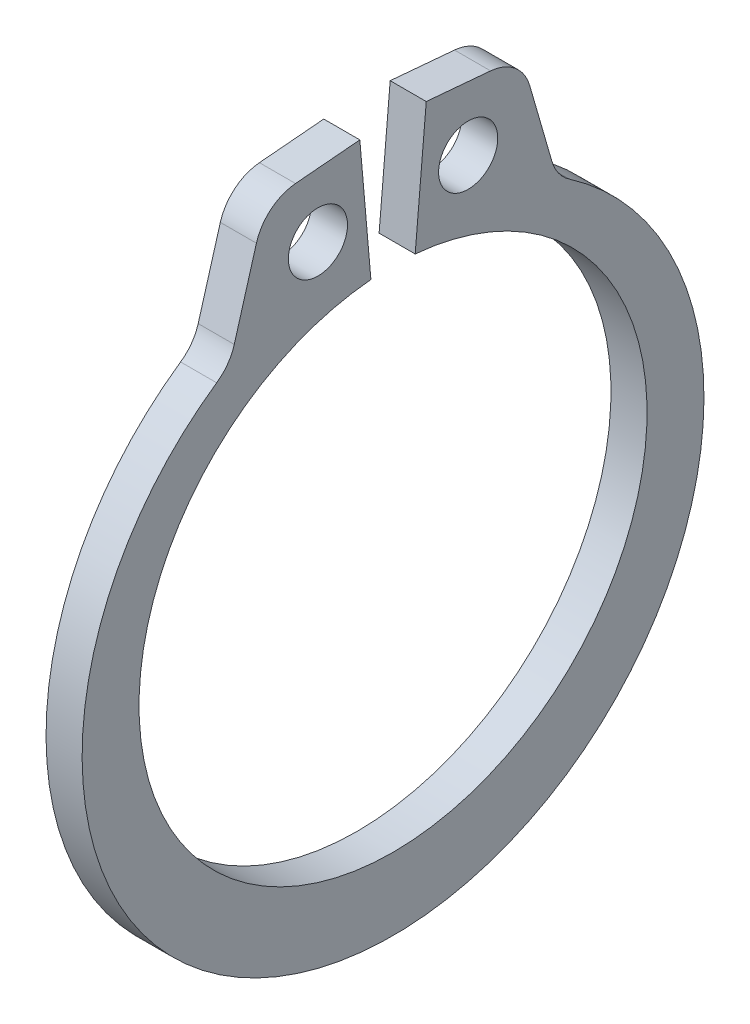
SolidWorks part; units mm, degrees
material "Cast Carbon Steel"
ref_plane "Front" through (0, 0, 0) normal (0, 0, 1) x (1, 0, 0)
ref_plane "Top" through (0, 0, 0) normal (0, 1, 0) x (1, 0, 0)
ref_plane "Right" through (0, 0, 0) normal (1, 0, 0) x (0, 0, -1)
sketch "Sketch1" plane through (0, 0, 0) normal (1, 0, 0) x (0, 0, -1)
  line L0 (0, 0) -> (0, 4.4704) construction
  line L1 (-0.3896, 4.4534) -> (-0.5844, 6.6801)
  line L2 (0.5844, 6.6801) -> (2.2545, 6.534)
  line L3 (2.2545, 6.534) -> (2.8753, 4.3867)
  line L4 (0.3896, 4.4534) -> (0.5844, 6.6801)
  line L5 (-0.5844, 6.6801) -> (-2.2545, 6.534)
  line L6 (-2.2545, 6.534) -> (-2.8753, 4.3867)
  line L7 (-2.8753, 4.3867) -> (-2.4507, 3.7388) construction
  line L8 (2.8753, 4.3867) -> (2.4507, 3.7388) construction
  line L9 (0, -4.4704) -> (0, -5.7404) construction
  line L10 (-2.2545, 6.534) -> (-0.3896, 4.4534) construction
  line L11 (0, 4.4704) -> (0, 6.7056) construction
  line L12 (-4.4704, 0) -> (4.4704, 0) construction
  circle A0 centre (0, 0) radius 4.4704 construction
  arc A1 (-0.3896, 4.4534) -> (0.3896, 4.4534) centre (0, 0) ccw
  circle A3 centre (0, 0) radius 7.493 construction
  circle A4 centre (-1.322, 5.4937) radius 0.5207
  circle A5 centre (1.322, 5.4937) radius 0.5207
  arc A6 (-2.8753, 4.3867) -> (2.8753, 4.3867) centre (0, -0.2686) ccw
  point P0 (0, -5.7404)
  dimension "A" = 8.9408
  dimension "Hole" = 1.0414
  dimension "Smin" = 0.7747
  dimension "H" = 2.2352
  dimension "D2" = 1.6764
  dimension "Angle" = 5
extrude "Extrude1" add sketch "Sketch1" along normal mid plane 0.635
fillet "Fillet1" radius 0.7874 4 edges at (0, 4.3867, 2.8753) (0, 4.3867, -2.8753) (0, 6.534, 2.2545) (0, 6.534, -2.2545)
sketch "Sketch2" plane through (0, 0, 0) normal (0, 0, 1) x (1, 0, 0)
  line L0 (-3.5433, 0) -> (9.1567, 0)
  line L1 (9.1567, 0) -> (9.1567, -4.7625)
  line L2 (-0.3683, -4.7625) -> (-3.2512, -4.7625)
  line L3 (9.1567, -4.7625) -> (0.3683, -4.7625)
  line L4 (0.3683, -4.7625) -> (0.3683, -4.4704)
  line L5 (0.3683, -4.4704) -> (-0.3683, -4.4704)
  line L6 (-0.3683, -4.4704) -> (-0.3683, -4.7625)
  line L7 (-0.3683, -4.7625) -> (-3.5433, -4.7625) construction
  line L8 (-3.5433, -4.7625) -> (-3.5433, 0) construction
  line L9 (9.1567, 0) -> (76.391, 0) construction
  line L10 (-3.2512, -4.7625) -> (-3.5433, -4.4704)
  line L11 (-3.5433, -4.4704) -> (-3.5433, 0)
  point P10 (0, -4.4704)
  dimension "D2" = 12.7
  dimension "D3" = 3.175
  dimension "D1" = 45
revolve "Revolve1" [suppressed] add sketch "Sketch2" angle 360 about L9
delete or keep bodies "Body-Delete1" [suppressed] type delete bodies bodies 122
equation "\"D2@Sketch2\" = \"D1@Extrude1\"*20"
equation "\"D3@Sketch2\" = \"D2@Sketch2\"/4"
equation "\"D2@Sketch1\" = \"H@Sketch1\"*.75"
